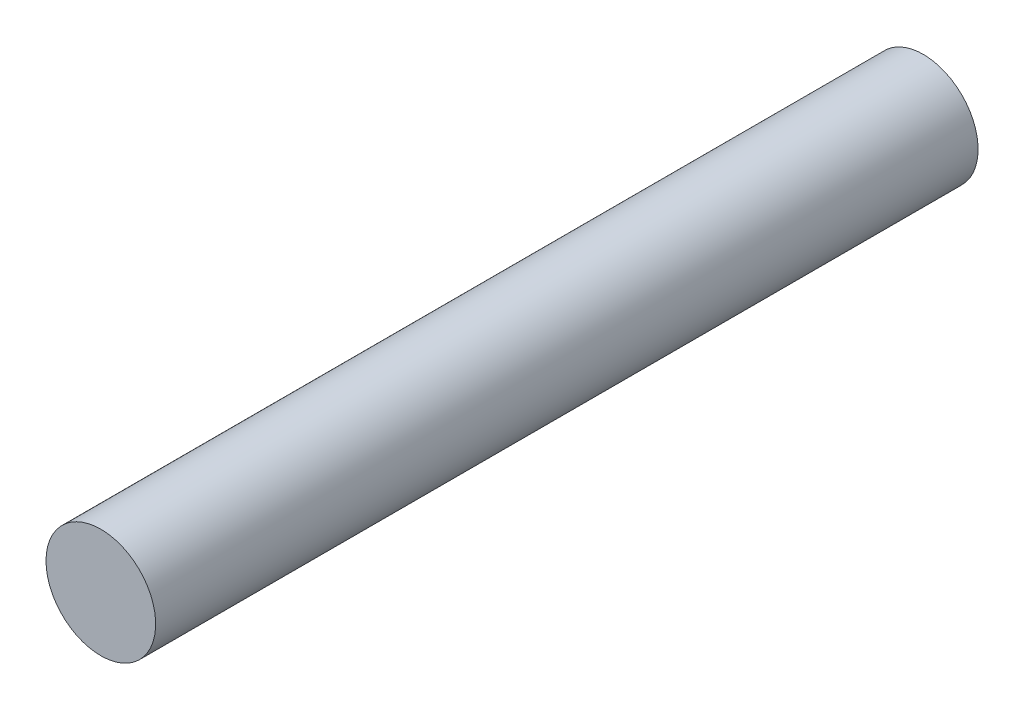
SolidWorks part; units mm, degrees
ref_plane "前视基准面" through (0, 0, 0) normal (0, 0, 1) x (1, 0, 0)
ref_plane "上视基准面" through (0, 0, 0) normal (0, 1, 0) x (1, 0, 0)
ref_plane "右视基准面" through (0, 0, 0) normal (1, 0, 0) x (0, 0, -1)
sketch "草图1" plane through (0, 0, 0) normal (0, 0, 1) x (1, 0, 0)
  circle A0 centre (0, 0) radius 3
  dimension "D1" = 6
extrude "凸台-拉伸1" add sketch "草图1" along normal blind 45
